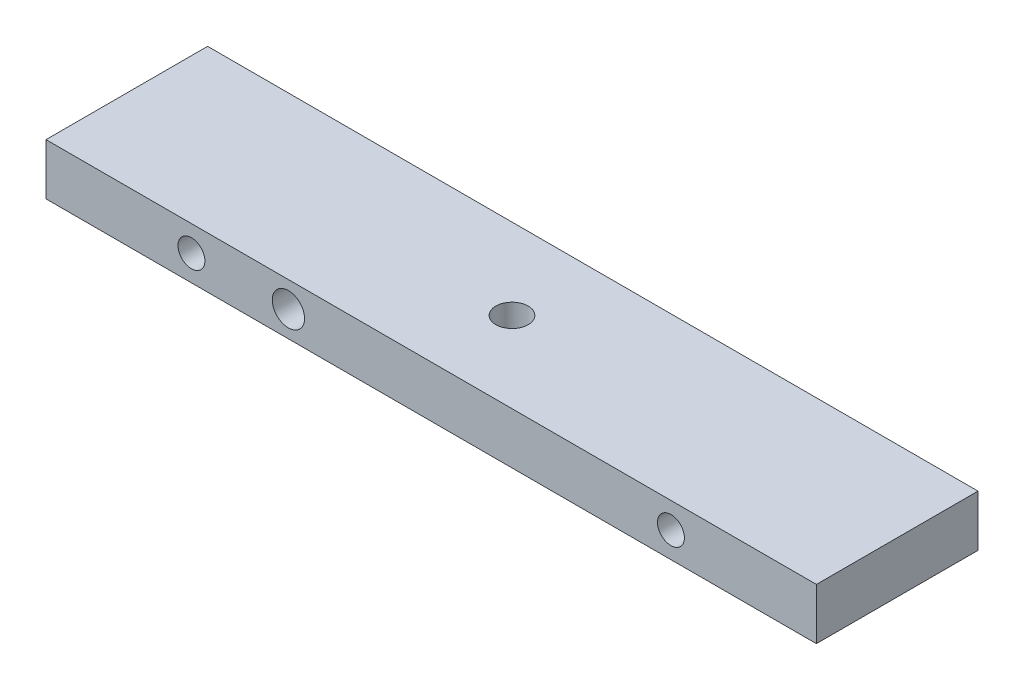
SolidWorks part; units mm, degrees
ref_plane "Plano frontal" through (0, 0, 0) normal (0, 0, 1) x (1, 0, 0)
ref_plane "Plano superior" through (0, 0, 0) normal (0, 1, 0) x (1, 0, 0)
ref_plane "Plano direito" through (0, 0, 0) normal (1, 0, 0) x (0, 0, -1)
sketch "Esboço1" plane through (0, 0, 0) normal (0, 0, 1) x (1, 0, 0)
  line L0 (25, 4.765) -> (-25, -4.765) construction
  line L1 (-25, 4.765) -> (25, 4.765)
  line L2 (-25, 4.765) -> (-25, -4.765)
  line L3 (-25, -4.765) -> (25, -4.765)
  line L4 (25, 4.765) -> (25, -4.765)
  dimension "D1" = 9.53
  dimension "D2" = 50
extrude "Ressalto-extrusão1" add sketch "Esboço1" along normal blind 30
sketch "Esboço2" plane through (0, 0, 30) normal (0, 0, 1) x (1, 0, 0)
  line L0 (-25, 0) -> (25, 0) construction
  line L1 (-25, 4.765) -> (-25, -4.765) construction
  line L2 (25, -4.765) -> (25, 4.765) construction
  circle A0 centre (-13, 0) radius 3
  dimension "D1" = 6
  dimension "D2" = 12
extrude "Corte-extrusão1" cut sketch "Esboço2" against normal through all
sketch "Esboço4" plane through (25, 0, 0) normal (1, 0, 0) x (0, 0, -1)
  line L4 (0, -4.765) -> (0, 4.765)
  line L5 (0, 4.765) -> (-30, 4.765)
  line L6 (-30, 4.765) -> (-30, -4.765)
  line L7 (-30, -4.765) -> (0, -4.765)
  line L8 (0, -4.765) -> (0, 4.765)
  line L9 (0, 4.765) -> (-30, 4.765)
  line L10 (-30, 4.765) -> (-30, -4.765)
  line L11 (-30, -4.765) -> (0, -4.765)
  dimension "D1" = 0
extrude "Ressalto-extrusão3" add sketch "Esboço4" along normal up to vertex (60.01 mm away)
sketch "Esboço5" plane through (-25, 0, 0) normal (-1, 0, 0) x (0, 0, 1)
  line L4 (0, 4.765) -> (0, -4.765)
  line L5 (0, -4.765) -> (30, -4.765)
  line L6 (30, -4.765) -> (30, 4.765)
  line L7 (30, 4.765) -> (0, 4.765)
  line L8 (0, 4.765) -> (0, -4.765)
  line L9 (0, -4.765) -> (30, -4.765)
  line L10 (30, -4.765) -> (30, 4.765)
  line L11 (30, 4.765) -> (0, 4.765)
  dimension "D1" = 0
extrude "Ressalto-extrusão4" add sketch "Esboço5" along normal up to vertex (33 mm away)
sketch "Esboço6" plane through (0, 0, 30) normal (0, 0, 1) x (1, 0, 0)
  circle A0 centre (-31, 0) radius 2.5
  circle A1 centre (58.01, 0) radius 2.5
extrude "Corte-extrusão2" cut sketch "Esboço6" against normal blind 10
sketch "Esboço7" plane through (0, 4.765, 0) normal (0, 1, 0) x (1, 0, 0)
  line L0 (-58, -15) -> (85.01, -15) construction
  line L1 (-58, -30) -> (-58, 0) construction
  line L2 (85.01, 0) -> (85.01, -30) construction
  line L3 (13.505, -30) -> (13.505, -15) construction
  line L4 (85.01, -30) -> (-58, -30) construction
  circle A0 centre (13.505, -15) radius 3
  dimension "D1" = 6
extrude "Corte-extrusão3" cut sketch "Esboço7" against normal up to next
